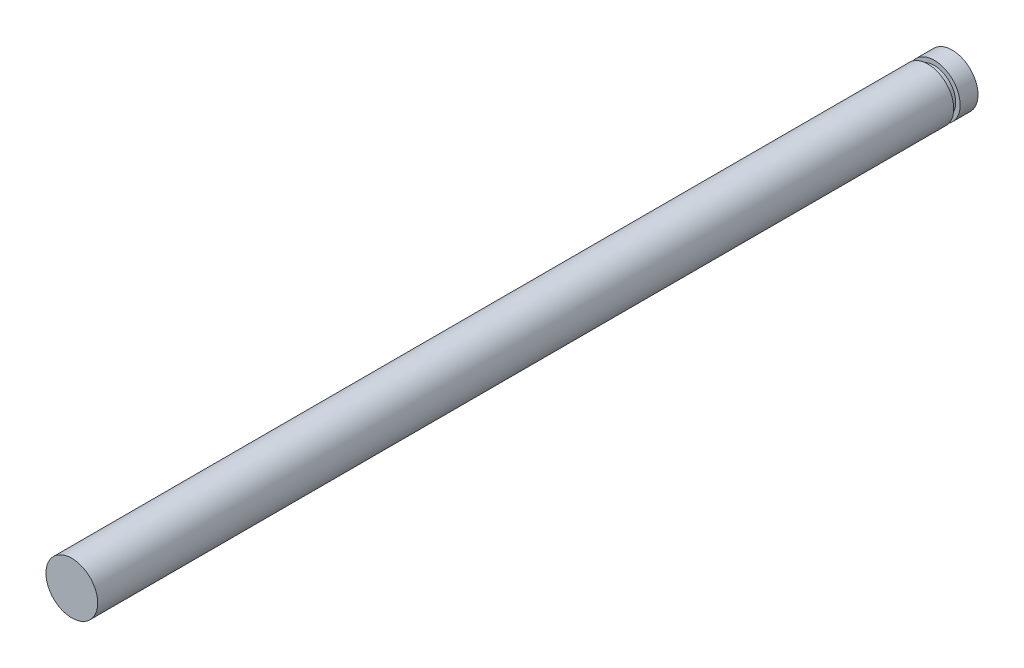
SolidWorks part; units mm, degrees
ref_plane "Front Plane" through (0, 0, 0) normal (0, 0, 1) x (1, 0, 0)
ref_plane "Top Plane" through (0, 0, 0) normal (0, 1, 0) x (1, 0, 0)
ref_plane "Right Plane" through (0, 0, 0) normal (1, 0, 0) x (0, 0, -1)
sketch "Sketch1" plane through (0, 0, 0) normal (1, 0, 0) x (0, 0, -1)
  line L0 (0, 0) -> (0, 18821.5164) construction
  line L1 (0, 0) -> (18821.5164, 0) construction
  line L2 (0, 0.725) -> (24, 0.725)
  line L3 (24, 0.725) -> (24, 0.6)
  line L4 (24, 0.6) -> (24.18, 0.6)
  line L5 (24.18, 0.6) -> (24.18, 0.725)
  line L6 (24.18, 0.725) -> (24.68, 0.725)
  line L7 (24.68, 0.725) -> (24.68, 0)
  line L8 (24.68, 0) -> (0, 0)
  line L9 (0, 0) -> (0, 0.725)
  dimension "D1" = 24
  dimension "D2" = 0.5
  dimension "D3" = 0.18
  dimension "D4" = 1.2
  dimension "D5" = 1.45
revolve "Revolve1" add sketch "Sketch1" angle 360 about L1
scale "Scale1" scale about centroid uniform scaling yes scale factor 25.4
